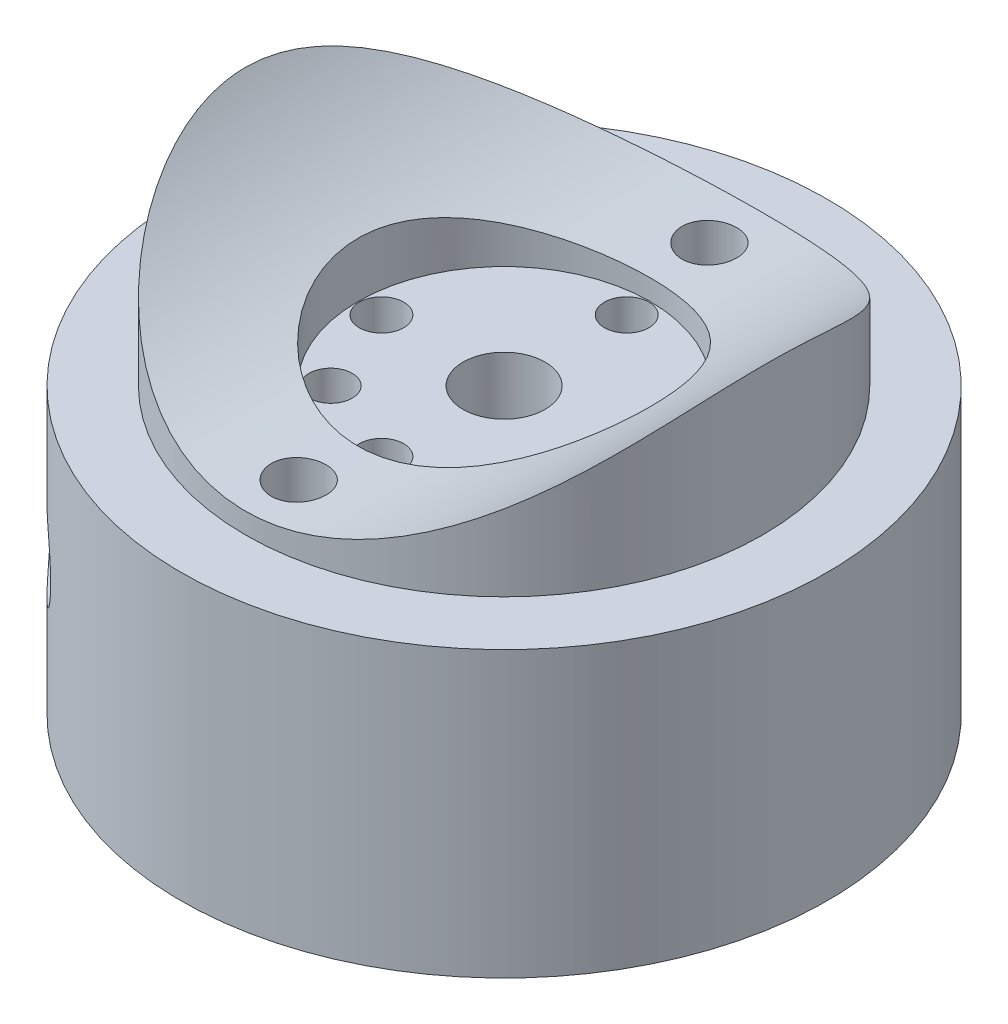
SolidWorks part; units mm, degrees
ref_plane "Front Plane" through (0, 0, 0) normal (0, 0, 1) x (1, 0, 0)
ref_plane "Top Plane" through (0, 0, 0) normal (0, 1, 0) x (1, 0, 0)
ref_plane "Right Plane" through (0, 0, 0) normal (1, 0, 0) x (0, 0, -1)
sketch "Sketch1" plane through (0, 0, 0) normal (0, 0, 1) x (1, 0, 0)
  line L0 (0, 0) -> (37.5, 0)
  line L1 (37.5, 0) -> (37.5, 33)
  line L2 (37.5, 33) -> (30, 33)
  line L3 (30, 33) -> (30, 50)
  line L4 (30, 50) -> (0, 50)
  line L5 (0, 50) -> (0, 0)
  dimension "D1" = 37.5
  dimension "D2" = 33
  dimension "D3" = 17
  dimension "D4" = 30
revolve "Revolve1" add sketch "Sketch1" angle 360 about L5
sketch "Sketch2" plane through (0, 0, 0) normal (0, 0, 1) x (1, 0, 0)
  circle A0 centre (0, 73.4864) radius 38.1
  dimension "D1" = 76.2
extrude "Cut-Extrude1" cut sketch "Sketch2" against normal through all both and the other way through all
sketch "Sketch3" plane through (0, 0, 0) normal (0, -1, 0) x (1, 0, 0)
  circle A0 centre (0, 0) radius 4.7625
  dimension "D1" = 9.525
extrude "Cut-Extrude2" cut sketch "Sketch3" against normal through all both
ref_plane "Plane1" through (-26.5165, 0, 26.5165) normal (-0.7071, 0, 0.7071) x (0, 1, 0)
sketch "Sketch7" plane through (-26.5165, 0, 26.5165) normal (-0.7071, 0, 0.7071) x (0, 1, 0)
  line L0 (0, 0) -> (33, 0) construction
  line L1 (33, -37.5) -> (33, 37.5) construction
  circle A0 centre (16.5, 0) radius 4.7625
  dimension "D1" = 9.525
extrude "Cut-Extrude5" cut sketch "Sketch7" against normal blind 22.5
sketch "Sketch4" plane through (0, 0, 0) normal (0, -1, 0) x (1, 0, 0)
  line L0 (0, 27) -> (0, -27) construction
  line L1 (-16.805, 0) -> (16.805, 0) construction
  line L2 (0, 16.805) -> (0, -16.805) construction
  circle A2 centre (0, 23.825) radius 3.175
  circle A3 centre (0, -23.825) radius 3.175
  circle A8 centre (-14.225, 0) radius 2.58
  circle A9 centre (0, 14.225) radius 2.58
  circle A10 centre (14.225, 0) radius 2.58
  circle A11 centre (0, -14.225) radius 2.58
  point P4 (0, 0)
  point P12 (0, 0)
  point P15 (0, 0)
  dimension "D2" = 6.35
  dimension "D5" = 5.16
  dimension "D1" = 54
  dimension "D3" = 33.61
  dimension "D4" = 33.61
extrude "Cut-Extrude3" cut sketch "Sketch4" against normal through all both and the other way through all
sketch "Sketch5" plane through (0, 33, 0) normal (0, 1, 0) x (1, 0, 0)
  circle A0 centre (0, 0) radius 16.94
  dimension "D1" = 33.88
extrude "Cut-Extrude4" cut sketch "Sketch5" along normal through all
sketch "Sketch8" plane through (0, 33, 0) normal (0, 1, 0) x (1, 0, 0)
  line L0 (-10.0586, -10.0586) -> (0, 0) construction
  line L1 (0, 0) -> (0, -14.225) construction
  circle A0 centre (0, 0) radius 14.225 construction
  circle A1 centre (-10.0586, -10.0586) radius 2.5
  dimension "D1" = 5
  dimension "D2" = 45
extrude "Cut-Extrude6" cut sketch "Sketch8" against normal blind 20
sketch "Sketch9" plane through (0, 0, 0) normal (0, -1, 0) x (1, 0, 0)
  circle A0 centre (0, 0) radius 9
  dimension "D1" = 18
extrude "Cut-Extrude7" cut sketch "Sketch9" against normal blind 18
